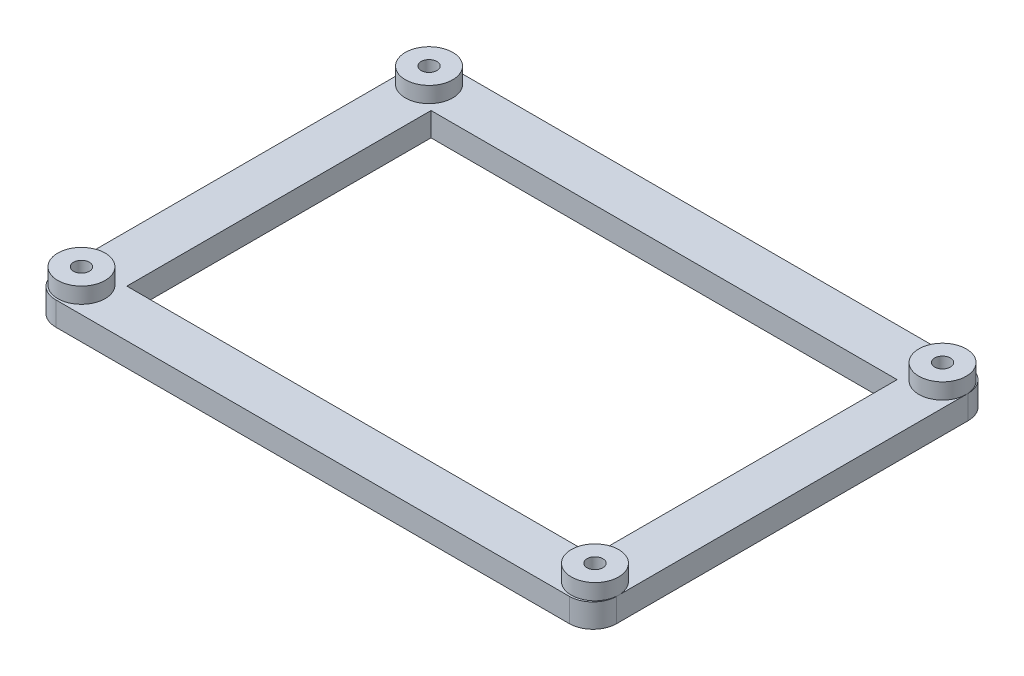
SolidWorks part; units mm, degrees
ref_plane "Front Plane" through (0, 0, 0) normal (0, 0, 1) x (1, 0, 0)
ref_plane "Top Plane" through (0, 0, 0) normal (0, 1, 0) x (1, 0, 0)
ref_plane "Right Plane" through (0, 0, 0) normal (1, 0, 0) x (0, 0, -1)
sketch "Sketch1" plane through (0, 0, 0) normal (0, 1, 0) x (1, 0, 0)
  line L0 (-29.5, -19.25) -> (-29.5, 19.25)
  line L1 (-35.5, -25.25) -> (35.5, -25.25)
  line L2 (-35.5, -25.25) -> (-35.5, 25.25)
  line L3 (-35.5, 25.25) -> (35.5, 25.25)
  line L4 (35.5, -25.25) -> (35.5, 25.25)
  line L5 (-35.5, -25.25) -> (35.5, 25.25) construction
  line L6 (-35.5, 25.25) -> (35.5, -25.25) construction
  line L7 (-29.5, 19.25) -> (29.5, 19.25)
  line L8 (29.5, -19.25) -> (29.5, 19.25)
  line L9 (-29.5, -19.25) -> (29.5, -19.25)
  line L11 (-32.5, -22) -> (32.5, -22) construction
  line L12 (-32.5, -22) -> (-32.5, 22) construction
  line L13 (-32.5, 22) -> (32.5, 22) construction
  line L14 (32.5, -22) -> (32.5, 22) construction
  line L15 (-32.5, -22) -> (32.5, 22) construction
  line L16 (-32.5, 22) -> (32.5, -22) construction
  circle A0 centre (-32.5, 22) radius 1
  circle A1 centre (-32.5, -22) radius 1
  circle A2 centre (32.5, -22) radius 1
  circle A3 centre (32.5, 22) radius 1
  point P0 (0, 0)
  point P10 (0, 0)
  dimension "D6" = 2
  dimension "D1" = 50.5
  dimension "D2" = 71
  dimension "D4" = 65
  dimension "D5" = 44
  dimension "D3" = 6
extrude "Boss-Extrude1" add sketch "Sketch1" along normal blind 3
sketch "Sketch2" plane through (0, 3, 0) normal (0, 1, 0) x (1, 0, 0)
  circle A0 centre (32.5, 22) radius 1 construction
  circle A1 centre (32.5, -22) radius 1 construction
  circle A2 centre (-32.5, -22) radius 1 construction
  circle A3 centre (-32.5, 22) radius 1 construction
  circle A4 centre (32.5, 22) radius 1
  circle A5 centre (32.5, -22) radius 1
  circle A6 centre (-32.5, -22) radius 1
  circle A7 centre (-32.5, 22) radius 1
  circle A8 centre (32.5, 22) radius 3
  circle A9 centre (32.5, -22) radius 3
  circle A10 centre (-32.5, -22) radius 3
  circle A11 centre (-32.5, 22) radius 3
  dimension "D1" = 2
extrude "Boss-Extrude2" add sketch "Sketch2" along normal blind 2
fillet "Fillet1" radius 3 4 edges at (35.5, 1.5, -25.25) (-35.5, 1.5, -25.25) (35.5, 1.5, 25.25) (-35.5, 1.5, 25.25)
